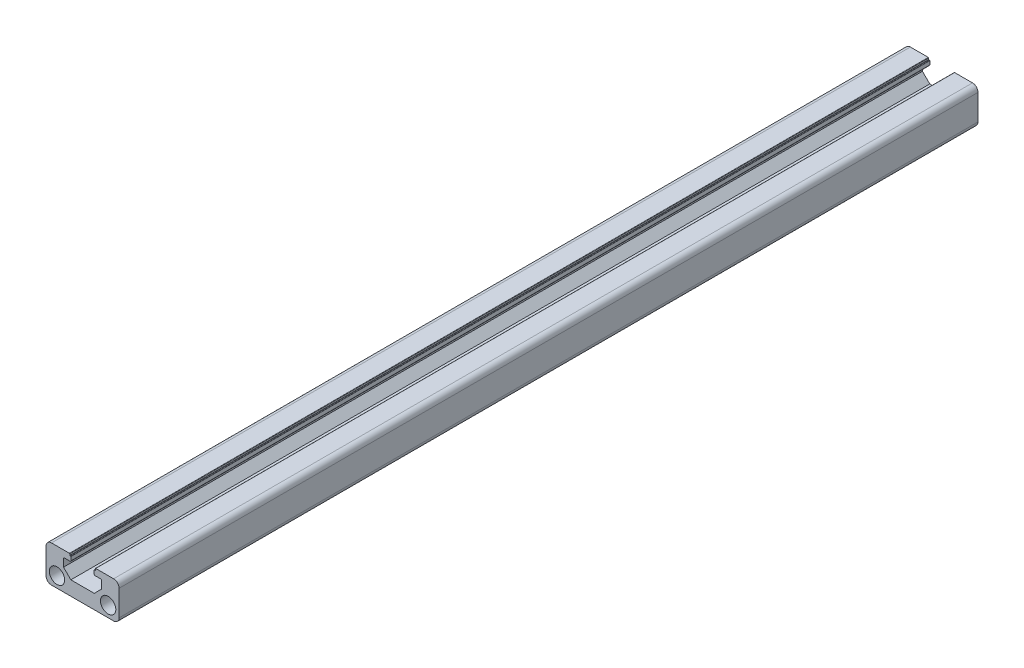
SolidWorks part; units mm, degrees
ref_plane "前视基准面" through (0, 0, 0) normal (0, 0, 1) x (1, 0, 0)
ref_plane "上视基准面" through (0, 0, 0) normal (0, 1, 0) x (1, 0, 0)
ref_plane "右视基准面" through (0, 0, 0) normal (1, 0, 0) x (0, 0, -1)
sketch "草图1" plane through (0, 0, 0) normal (0, 0, 1) x (1, 0, 0)
  line L0 (0, 0) -> (13.0081, 0) construction
  line L1 (0, 0) -> (0, 5.2809) construction
  line L3 (8.5, -3.9) -> (-8.5, -3.9)
  line L4 (-10, -2.4) -> (-10, 4.6)
  line L5 (-8.5, 6.1) -> (-3.5, 6.1)
  line L6 (-3.5, 6.1) -> (-3.5, 5.6)
  line L7 (-3.5, 5.6) -> (-3.2, 5.6)
  line L8 (-3.2, 5.6) -> (-3.2, 4.3)
  line L9 (-3.2, 4.3) -> (-5.2, 4.3)
  line L10 (-5.2, 4.3) -> (-5.2, 2)
  line L11 (-5.2, 2) -> (-3.2, 0)
  line L12 (-3.2, 0) -> (3.2, 0)
  line L13 (5.2, 2) -> (3.2, 0)
  line L14 (5.2, 4.3) -> (5.2, 2)
  line L15 (3.2, 4.3) -> (5.2, 4.3)
  line L16 (3.2, 5.6) -> (3.2, 4.3)
  line L17 (3.5, 5.6) -> (3.2, 5.6)
  line L18 (3.5, 6.1) -> (3.5, 5.6)
  line L19 (8.5, 6.1) -> (3.5, 6.1)
  line L20 (10, -2.4) -> (10, 4.6)
  arc A0 (-8.5, 6.1) -> (-10, 4.6) centre (-8.5, 4.6) ccw
  arc A1 (-10, -2.4) -> (-8.5, -3.9) centre (-8.5, -2.4) ccw
  circle A2 centre (-7, -0.9) radius 2.1
  circle A3 centre (7, -0.9) radius 2.1
  arc A4 (10, -2.4) -> (8.5, -3.9) centre (8.5, -2.4) cw
  arc A5 (8.5, 6.1) -> (10, 4.6) centre (8.5, 4.6) cw
  point P43 (0, 0)
  point P49 (0, -3.9)
  dimension "D5" = 1.5
  dimension "D1" = 1.5
  dimension "D8" = 4.2
  dimension "D2" = 3.2
  dimension "D3" = 1.8
  dimension "D4" = 10
  dimension "D6" = 10
  dimension "D7" = 3.9
  dimension "D9" = 3
  dimension "D10" = 3
  dimension "D11" = 3.5
  dimension "D12" = 0.5
  dimension "D13" = 3.2
  dimension "D14" = 135
  dimension "D15" = 2
extrude "凸台-拉伸1" add sketch "草图1" along normal blind 235
fillet "圆角1" radius 0.1 4 edges at (-3.5, 6.1, 117.5) (-3.2, 5.6, 117.5) (3.5, 6.1, 117.5) (3.2, 5.6, 117.5)
fillet "圆角2" radius 0.2 4 edges at (-5.2, 4.3, 117.5) (5.2, 4.3, 117.5) (-3.2, 4.3, 117.5) (3.2, 4.3, 117.5)
